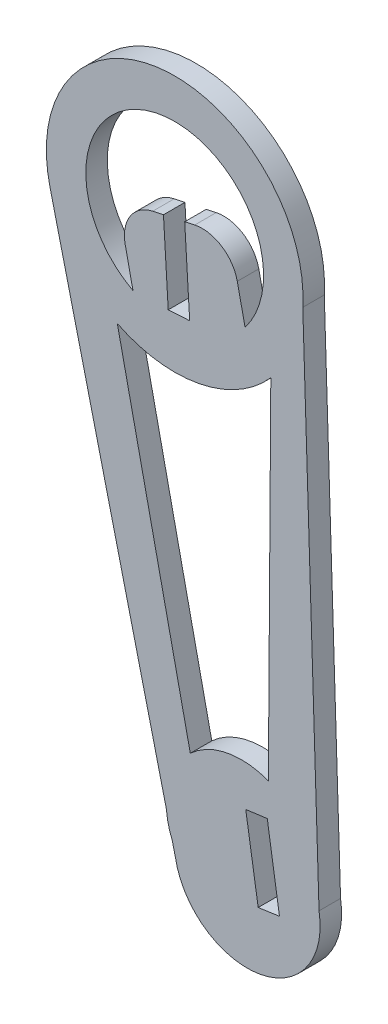
SolidWorks part; units mm, degrees
ref_plane "Front" through (0, 0, 0) normal (0, 0, 1) x (1, 0, 0)
ref_plane "Top" through (0, 0, 0) normal (0, 1, 0) x (1, 0, 0)
ref_plane "Right" through (0, 0, 0) normal (1, 0, 0) x (0, 0, -1)
sketch "Sketch1" plane through (0, 0, 0) normal (0, 0, 1) x (1, 0, 0)
  line L0 (-1733.906, 29.6977) -> (-1717.6601, -37.3561)
  line L1 (-1716.8469, -40.7124) -> (-1716.4172, -42.4861)
  line L4 (-1698.6351, 32.8358) -> (-1696.3659, -38.964)
  line L5 (-1703.0967, 22.0959) -> (-1703.4386, -26.7988)
  line L6 (-1724.5173, 17.9431) -> (-1714.3327, -28.9061)
  line L8 (-1719.5825, 33.9776) -> (-1713.7177, 35.2441)
  line L10 (-1707.7749, 31.4121) -> (-1706.6896, 26.3861)
  line L11 (-1723.4144, 28.0349) -> (-1722.3291, 23.0089)
  arc A0 (-1698.6351, 32.8358) -> (-1733.906, 29.6977) centre (-1716.5106, 33.9651) ccw
  arc A1 (-1706.6896, 26.3861) -> (-1722.3291, 23.0089) centre (-1716.5106, 33.9651) ccw
  arc A2 (-1716.4172, -42.4861) -> (-1696.3659, -38.964) centre (-1706.3915, -40.7251) ccw
  arc A3 (-1724.5173, 17.9431) -> (-1703.0967, 22.0959) centre (-1716.5106, 33.9651) ccw
  arc A4 (-1719.5825, 33.9776) -> (-1723.4144, 28.0349) centre (-1718.5271, 29.0903) ccw
  arc A5 (-1707.7749, 31.4121) -> (-1713.7177, 35.2441) centre (-1712.6623, 30.3567) ccw
  arc A7 (-1717.6601, -37.3561) -> (-1716.8469, -40.7124) centre (-1707.1942, -36.5971) ccw
  arc A8 (-1703.4386, -26.7988) -> (-1714.3327, -28.9061) centre (-1707.1942, -36.5971) ccw
  dimension "D5" = 5
  dimension "D1" = 8
  dimension "D4" = 8
extrude "Base-Extrude" add sketch "Sketch1" along normal blind 3
sketch "Sketch2" plane through (0, 0, 3) normal (0, 0, 1) x (1, 0, 0)
  line L1 (-1715.4507, 40.6296) -> (-1714.419, 23.3251)
  line L3 (-1714.419, 23.3251) -> (-1717.4137, 23.1466)
  line L4 (-1717.4137, 23.1466) -> (-1718.0089, 33.1288)
  line L6 (-1718.0089, 33.1288) -> (-1718.4454, 40.4511)
  line L7 (-1718.4454, 40.4511) -> (-1715.4507, 40.6296)
extrude "Cut-Extrude2" cut sketch "Sketch2" against normal blind 98
sketch "Sketch4" plane through (0, 0, 0) normal (0, 0, -1) x (-1, 0, 0)
  line L0 (1704.8585, -42.8081) -> (1706.5947, -31.8211)
  line L1 (1704.8585, -42.8081) -> (1701.8893, -42.3795)
  line L2 (1701.8893, -42.3795) -> (1703.5879, -31.4245)
  line L4 (1703.5879, -31.4245) -> (1706.5947, -31.8211)
extrude "Cut-Extrude6" cut sketch "Sketch4" against normal blind 32
